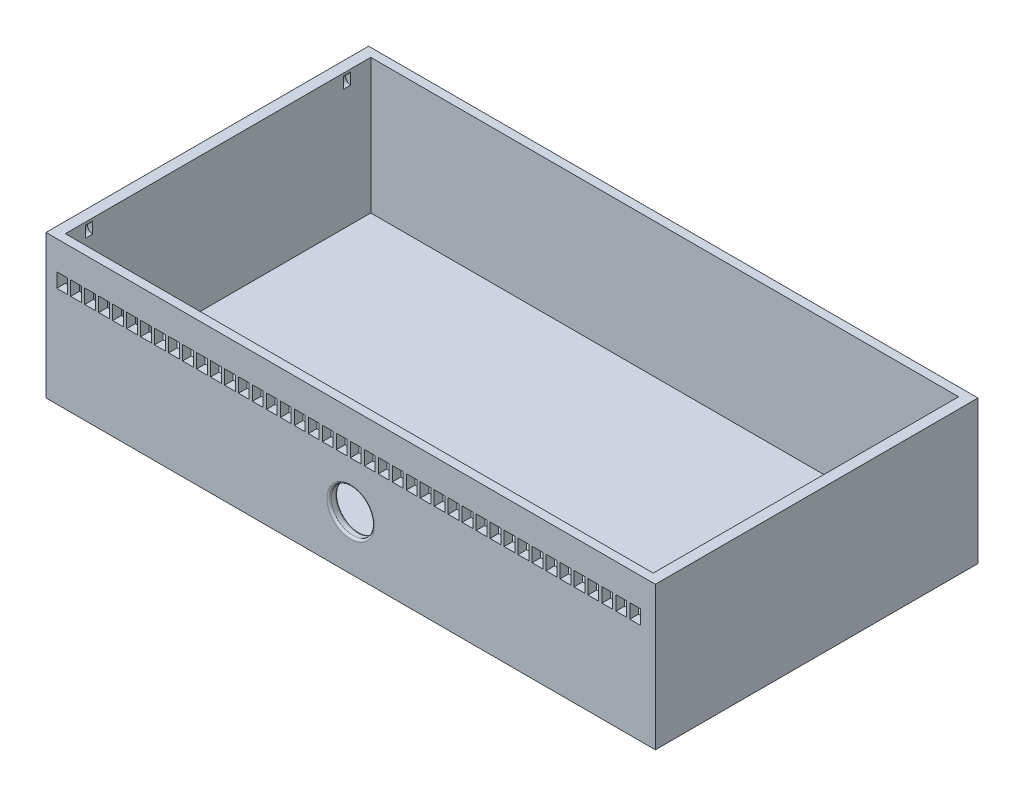
SolidWorks part; units mm, degrees
ref_plane "Front Plane" through (0, 0, 0) normal (0, 0, 1) x (1, 0, 0)
ref_plane "Top Plane" through (0, 0, 0) normal (0, 1, 0) x (1, 0, 0)
ref_plane "Right Plane" through (0, 0, 0) normal (1, 0, 0) x (0, 0, -1)
sketch "Sketch1" plane through (0, 0, 0) normal (0, 1, 0) x (1, 0, 0)
  line L1 (-107.95, -57.15) -> (107.95, -57.15)
  line L2 (-107.95, -57.15) -> (-107.95, 57.15)
  line L3 (-107.95, 57.15) -> (107.95, 57.15)
  line L4 (107.95, -57.15) -> (107.95, 57.15)
  line L5 (-107.95, -57.15) -> (107.95, 57.15) construction
  line L6 (-107.95, 57.15) -> (107.95, -57.15) construction
  point P0 (0, 0)
  dimension "D1" = 215.9
  dimension "D2" = 114.3
extrude "Boss-Extrude1" add sketch "Sketch1" along normal blind 50.8
sketch "Sketch2" plane through (0, 50.8, 0) normal (0, 1, 0) x (1, 0, 0)
  line L0 (-107.95, 57.15) -> (-107.95, -57.15) construction
  line L1 (-104.14, -54.102) -> (104.14, -54.102)
  line L2 (-104.14, -54.102) -> (-104.14, 54.102)
  line L3 (-104.14, 54.102) -> (104.14, 54.102)
  line L4 (104.14, -54.102) -> (104.14, 54.102)
  line L5 (-104.14, -54.102) -> (104.14, 54.102) construction
  line L6 (-104.14, 54.102) -> (104.14, -54.102) construction
  line L7 (107.95, 57.15) -> (-107.95, 57.15) construction
  line L8 (-107.95, -57.15) -> (107.95, -57.15) construction
  line L9 (107.95, -57.15) -> (107.95, 57.15) construction
  point P0 (0, 0)
  dimension "D1" = 3.81
  dimension "D2" = 3.048
  dimension "D3" = 3.048
  dimension "D4" = 3.81
extrude "Cut-Extrude1" cut sketch "Sketch2" against normal blind 47.752
sketch "Sketch3" plane through (0, 0, 57.15) normal (0, 0, 1) x (1, 0, 0)
  line L8 (-107.95, 50.8) -> (-107.95, 0) construction
  line L9 (-104.14, 40.64) -> (-100.33, 40.64)
  line L10 (-104.14, 40.64) -> (-104.14, 35.56)
  line L11 (-104.14, 35.56) -> (-100.33, 35.56)
  line L12 (-100.33, 40.64) -> (-100.33, 35.56)
  line L13 (-107.95, 50.8) -> (107.95, 50.8) construction
  dimension "D1" = 3.81
  dimension "D3" = 10.16
  dimension "D5" = 3.81
  dimension "D6" = 5.08
extrude "Cut-Extrude2" cut sketch "Sketch3" against normal blind 7.62
pattern_linear "LPattern1" count 42 spacing 4.953 along (1, 0, 0) of "Cut-Extrude2"
sketch "Sketch4" plane through (0, 0, 57.15) normal (0, 0, 1) x (1, 0, 0)
  line L0 (-107.95, 50.8) -> (107.95, 50.8) construction
  circle A0 centre (0, 19.05) radius 7.62
  dimension "D1" = 15.24
  dimension "D2" = 31.75
extrude "Cut-Extrude3" cut sketch "Sketch4" against normal blind 7.62
sketch "Sketch6" plane through (0, 0, -57.15) normal (0, 0, -1) x (-1, 0, 0)
  line L0 (-107.95, 50.8) -> (107.95, 50.8) construction
  line L1 (-107.95, 50.8) -> (-107.95, 0) construction
  circle A0 centre (-91.44, 15.24) radius 10.668
  dimension "D1" = 35.56
  dimension "D2" = 16.51
extrude "Cut-Extrude5" cut sketch "Sketch6" against normal blind 7.62
ref_plane "Plane1" through (0, 0, -57.15) normal (0, 0, -1) x (-1, 0, 0)
ref_plane "Plane2" through (0, 0, -44.45) normal (0, 0, -1) x (-1, 0, 0)
ref_plane "Plane3" through (0, 0, 44.45) normal (0, 0, -1) x (-1, 0, 0)
sketch "Sketch12" plane through (0, 0, 44.45) normal (0, 0, -1) x (-1, 0, 0)
  line L1 (107.95, 47.625) -> (104.14, 47.625) construction
  line L2 (107.95, 50.8) -> (107.95, 0) construction
  line L3 (104.14, 3.048) -> (104.14, 50.8) construction
  line L4 (107.95, 50.8) -> (95.93, 50.8) construction
  line L5 (-104.14, 50.8) -> (104.14, 50.8) construction
  circle A0 centre (104.14, 47.625) radius 1.778
  dimension "D1" = 3.175
  dimension "D2" = 3.556
extrude "Cut-Extrude7" cut sketch "Sketch12" against normal blind 2.54
mirror "Mirror1" about plane through (0, 0, 0) normal (1, 0, 0) of "Cut-Extrude7"
mirror "Mirror2" about plane through (0, 0, 0) normal (0, 0, 1) of "Mirror1", "Cut-Extrude7"
fillet "Fillet1" radius 0.762 4 edges at (7.62, 19.05, 57.15) (80.772, 15.24, -54.102) (7.62, 19.05, 54.102) (80.772, 15.24, -57.15)
fillet "Fillet3" radius 0.762 4 edges at (104.14, 49.403, 45.72) (104.14, 49.403, -45.72) (-104.14, 49.403, -45.72) (-104.14, 49.403, 45.72)
